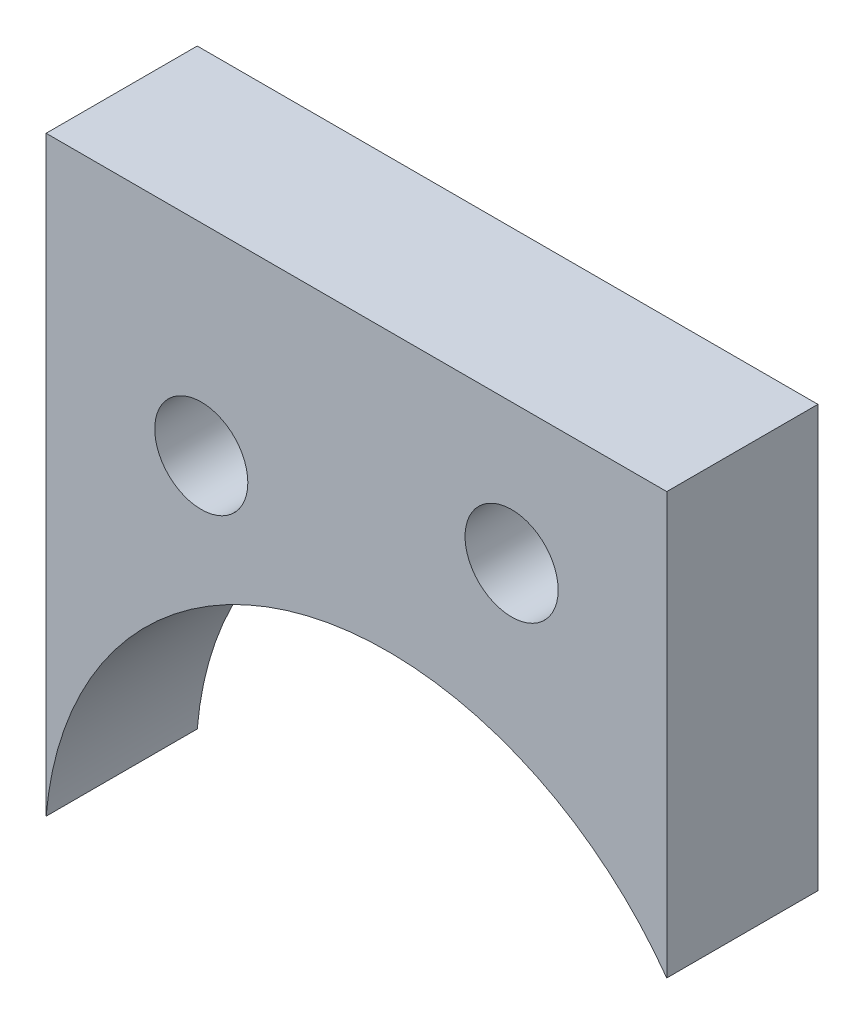
SolidWorks part; units mm, degrees
ref_plane "Front Plane" through (0, 0, 0) normal (0, 0, 1) x (1, 0, 0)
ref_plane "Top Plane" through (0, 0, 0) normal (0, 1, 0) x (1, 0, 0)
ref_plane "Right Plane" through (0, 0, 0) normal (1, 0, 0) x (0, 0, -1)
sketch "Sketch1" plane through (0, 0, 0) normal (0, 0, 1) x (1, 0, 0)
  line L2 (0, 0.9394) -> (0, 20)
  line L3 (0, 20) -> (20, 20)
  line L4 (20, 6.4251) -> (20, 20)
  circle A0 centre (5, 13.5) radius 1.5
  circle A1 centre (15, 15.5) radius 1.5
  arc A2 (20, 6.4251) -> (0, 0.9394) centre (11.01, 0) ccw
  point P0 (0, 0)
extrude "Boss-Extrude1" add sketch "Sketch1" along normal blind 4.87
